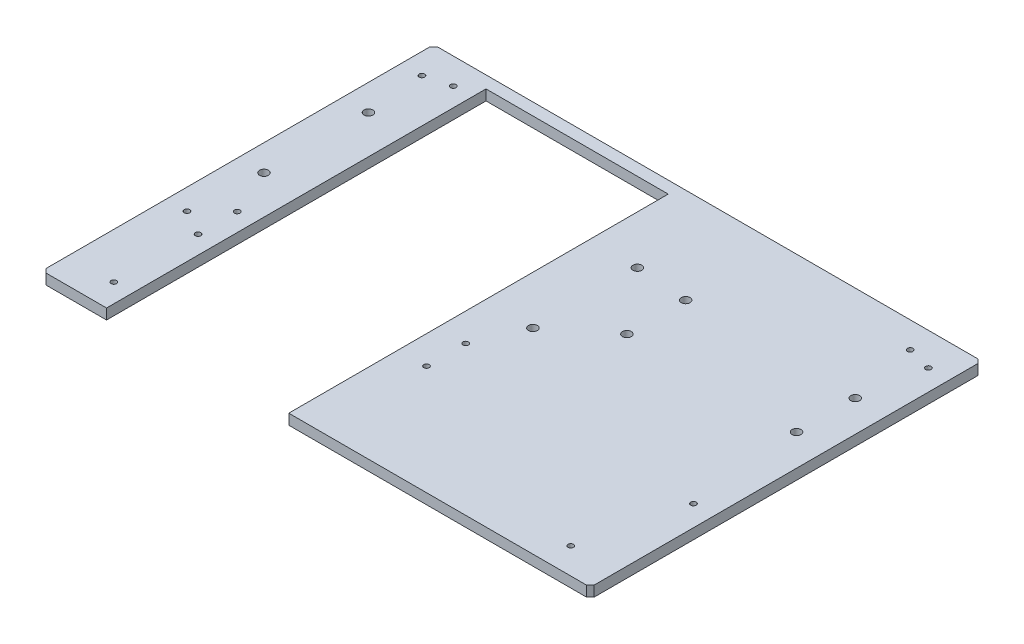
SolidWorks part; units mm, degrees
material "SS400"
ref_plane "Front Plane" through (0, 0, 0) normal (0, 0, 1) x (1, 0, 0)
ref_plane "Top Plane" through (0, 0, 0) normal (0, 1, 0) x (1, 0, 0)
ref_plane "Right Plane" through (0, 0, 0) normal (1, 0, 0) x (0, 0, -1)
sketch "Sketch1" plane through (0, 0, 0) normal (0, 1, 0) x (1, 0, 0)
  line L1 (-210, -150) -> (210, -150)
  line L2 (-210, -150) -> (-210, 150)
  line L3 (-210, 150) -> (210, 150)
  line L4 (210, -150) -> (210, 150)
  line L5 (-210, -150) -> (210, 150) construction
  line L6 (-210, 150) -> (210, -150) construction
  point P0 (0, 0)
  dimension "D1" = 300
  dimension "D2" = 420
extrude "Boss-Extrude1" add sketch "Sketch1" along normal mid plane 8
chamfer "Chamfer1" distance 3 angle 45 4 edges at (-210, 0, -150) (-210, 0, 150) (210, 0, -150) (210, 0, 150)
sketch "Sketch2" plane through (0, 4, 0) normal (0, 1, 0) x (1, 0, 0)
  line L0 (-210, 147) -> (-210, -147) construction
  line L1 (207, 150) -> (-207, 150) construction
  line L2 (210, -147) -> (210, 147) construction
  line L3 (0, -150) -> (0, -168.2555) construction
  line L4 (-207, -150) -> (207, -150) construction
  line L5 (210, 0) -> (225.654, 0) construction
  line L6 (-210, 35) -> (-215.531, 35) construction
  circle A0 centre (-190, 0) radius 5.3266
  circle A1 centre (16, 0) radius 5.3266
  circle A2 centre (-190, 80) radius 5.3266
  circle A3 centre (16, 80) radius 5.3266
  circle A4 centre (186, 77) radius 5.7937
  circle A5 centre (56, 77) radius 6.3731
  circle A6 centre (186, 32) radius 5.7937
  circle A7 centre (56, 32) radius 6.3731
  circle A8 centre (-175, -130) radius 5.7019
  circle A9 centre (-175, 130) radius 5.7019
  circle A10 centre (175, -130) radius 5.7019
  circle A11 centre (175, 130) radius 5.7019
  circle A12 centre (-174.5, -66) radius 4.7955
  circle A13 centre (0.5, -66) radius 4.7955
  circle A14 centre (-174.5, -36) radius 4.7955
  circle A15 centre (0.5, -36) radius 4.7955
  circle A16 centre (-194, 125) radius 2.3156
  circle A17 centre (-194, -55) radius 2.3156
  circle A18 centre (194, 125) radius 2.3156
  circle A19 centre (194, -55) radius 2.3156
  dimension "D4" = 20
  dimension "D5" = 206
  dimension "D6" = 70
  dimension "D8" = 130
  dimension "D9" = 73
  dimension "D13" = 20
  dimension "D17" = 84
  dimension "D18" = 30
  dimension "D19" = 175
  dimension "D20" = 16
  dimension "D3" = 80
  dimension "D7" = 24
  dimension "D11" = 45
  dimension "D12" = 35
  dimension "D16" = 35.5
  dimension "D21" = 115
  dimension "D22" = 180
  dimension "D1" = 2
  dimension "D2" = 2
  dimension "D10" = 2
  dimension "D14" = 2
  dimension "D15" = 2
hole_wizard "M8 Tapped Hole1" positions "3DSketch1" profile "Sketch3" tap size "M8" standard "ISO"
sketch3d "3DSketch1"
  point P0 (-190, 4, -80)
  point P3 (16, 4, -80)
  point P6 (16, 4, 0)
  point P9 (-190, 4, 0)
  point P13 (56, 4, -32)
  point P16 (186, 4, -32)
  point P19 (186, 4, -77)
  point P22 (56, 4, -77)
sketch "Sketch3" plane through (-190, 4, -80) normal (1, 0, 0) x (0, 0, 1)
  line L0 (0, 0) -> (0, 21.7929)
  line L1 (0, 21.7929) -> (3.4, 19.75)
  line L2 (3.4, 19.75) -> (3.4, 0)
  line L5 (3.4, 0) -> (0, 0)
  line L10 (0, 21.7929) -> (-3.4, 19.75) construction
  line L11 (0, -6.35) -> (0, 107.95) construction
  dimension "Tap Drill Dia." = 6.8
  dimension "Tap Drill Depth" = 19.75
  dimension "Drill Angle" = 118
cosmetic thread "Hole Thread1" parameters "D1"=8, "D2"=8
cosmetic thread "Hole Thread2" parameters "D1"=8, "D2"=8
cosmetic thread "Hole Thread3" parameters "D1"=8, "D2"=8
cosmetic thread "Hole Thread4" parameters "D1"=8, "D2"=8
cosmetic thread "Hole Thread5" parameters "D1"=8, "D2"=8
cosmetic thread "Hole Thread6" parameters "D1"=8, "D2"=8
cosmetic thread "Hole Thread7" parameters "D1"=8, "D2"=8
cosmetic thread "Hole Thread8" parameters "D1"=8, "D2"=8
hole_wizard "M5 Tapped Hole1" positions "Sketch5" profile "Sketch4" tap size "M5" standard "ISO"
sketch "Sketch5" plane through (0, 4, 0) normal (0, 1, 0) x (-1, 0, 0)
  point P1 (175, 130)
  point P4 (-175, 130)
  point P7 (-175, -130)
  point P10 (175, -130)
  point P13 (194, -125)
  point P16 (194, 55)
  point P19 (-194, 55)
  point P22 (-194, -125)
  point P25 (174.5, 66)
  point P28 (174.5, 36)
  point P31 (-0.5, 36)
  point P34 (-0.5, 66)
sketch "Sketch4" plane through (-175, 4, 130) normal (1, 0, 0) x (0, 0, 1)
  line L0 (0, 0) -> (0, 13.6618)
  line L1 (0, 13.6618) -> (2.1, 12.4)
  line L2 (2.1, 12.4) -> (2.1, 0)
  line L5 (2.1, 0) -> (0, 0)
  line L10 (0, 13.6618) -> (-2.1, 12.4) construction
  line L11 (0, -6.35) -> (0, 107.95) construction
  dimension "Tap Drill Dia." = 4.2
  dimension "Tap Drill Depth" = 12.4
  dimension "Drill Angle" = 118
cosmetic thread "Hole Thread9" parameters "D1"=8, "D2"=5
cosmetic thread "Hole Thread10" parameters "D1"=8, "D2"=5
cosmetic thread "Hole Thread11" parameters "D1"=8, "D2"=5
cosmetic thread "Hole Thread12" parameters "D1"=8, "D2"=5
cosmetic thread "Hole Thread18" parameters "D1"=8, "D2"=5
cosmetic thread "Hole Thread19" parameters "D1"=8, "D2"=5
cosmetic thread "Hole Thread20" parameters "D1"=8, "D2"=5
cosmetic thread "Hole Thread21" parameters "D1"=8, "D2"=5
cosmetic thread "Hole Thread22" parameters "D1"=8, "D2"=5
cosmetic thread "Hole Thread23" parameters "D1"=8, "D2"=5
cosmetic thread "Hole Thread24" parameters "D1"=8, "D2"=5
cosmetic thread "Hole Thread25" parameters "D1"=8, "D2"=5
sketch "Sketch6" plane through (0, 4, 0) normal (0, 1, 0) x (1, 0, 0)
  line L1 (-160.6096, 140.7011) -> (-21.0269, 140.7011)
  line L2 (-160.6096, 140.7011) -> (-160.6096, -163.0701)
  line L3 (-160.6096, -163.0701) -> (-21.0269, -163.0701)
  line L4 (-21.0269, 140.7011) -> (-21.0269, -163.0701)
extrude "Cut-Extrude1" cut sketch "Sketch6" against normal blind 10
equation "\"Mass Kg\"= \"SW-Mass\""
